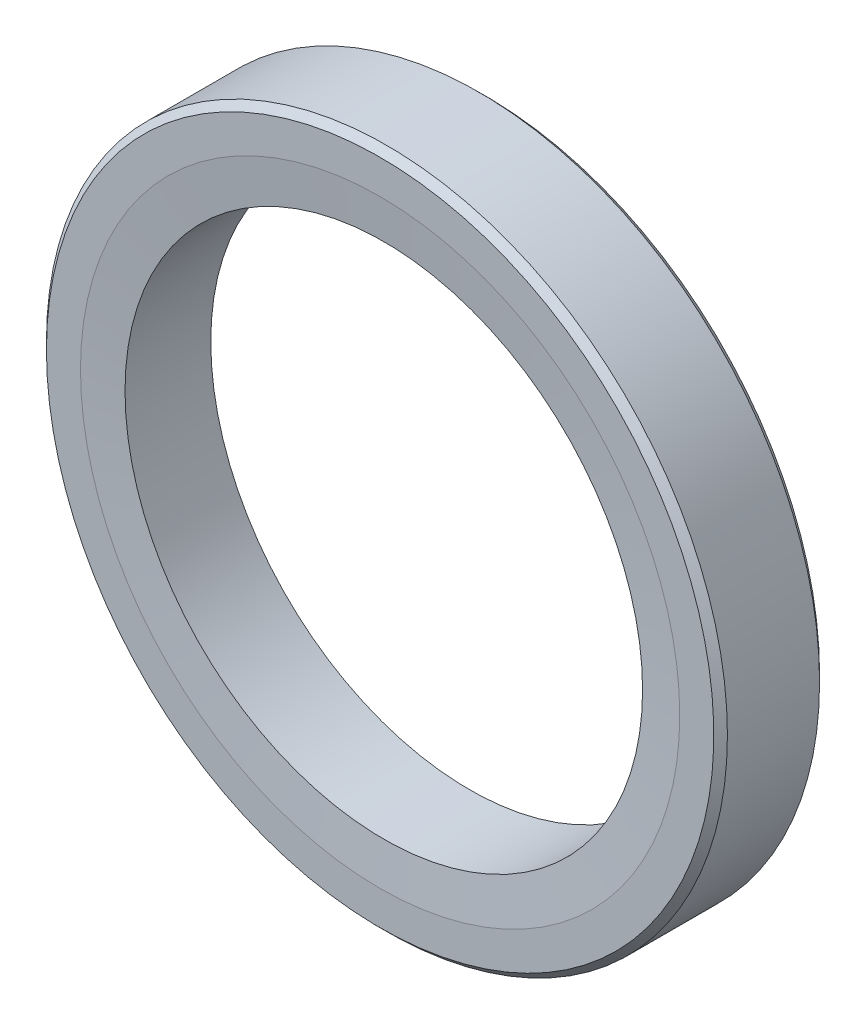
SolidWorks part; units mm, degrees
material "Brass"
ref_plane "Front Plane" through (0, 0, 0) normal (0, 0, 1) x (1, 0, 0)
ref_plane "Top Plane" through (0, 0, 0) normal (0, 1, 0) x (1, 0, 0)
ref_plane "Right Plane" through (0, 0, 0) normal (1, 0, 0) x (0, 0, -1)
sketch "Sketch1" plane through (0, 0, 0) normal (1, 0, 0) x (0, 0, -1)
  line L0 (-3.8832, 25) -> (3.8832, 25)
  line L1 (-3.8832, 25) -> (-3.8832, 22)
  line L2 (3.8832, 25) -> (3.8832, 22)
  line L3 (-3.6127, 19) -> (2.6826, 19)
  line L4 (2.6826, 19) -> (3.8832, 22)
  line L5 (-3.8832, 22) -> (-3.6127, 19)
  point P2 (0, 25)
  dimension "D5" = 95.151
  dimension "D1" = 7.7663
  dimension "D2" = 6
  dimension "D3" = 3
  dimension "D4" = 3
  dimension "D6" = 158.19
  dimension "D7" = 25
ref_axis "Axis1" through (0, 0, 4.95) along (0, 0, -1)
revolve "Revolve1" add sketch "Sketch1" angle 360 about axis through (0, 0, 4.95) along (0, 0, -1)
chamfer "Chamfer1" distance 0.5 angle 45 2 edges at (25, 0, -3.8832) (25, 0, 3.8832)
